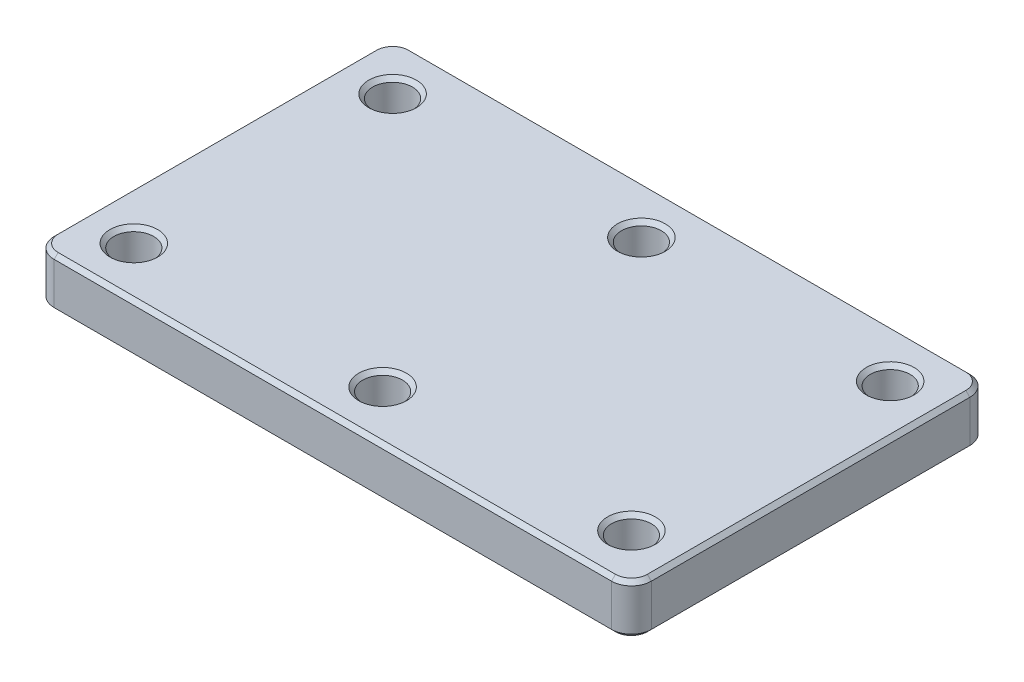
SolidWorks part; units mm, degrees
ref_plane "前基準面" through (0, 0, 0) normal (0, 0, 1) x (1, 0, 0)
ref_plane "上基準面" through (0, 0, 0) normal (0, 1, 0) x (1, 0, 0)
ref_plane "右基準面" through (0, 0, 0) normal (1, 0, 0) x (0, 0, -1)
ref_plane "平面1"
sketch "草圖1" plane through (0, 0, 0) normal (0, 1, 0) x (-1, 0, 0)
  line L0 (150, -90) -> (-150, -90)
  line L1 (-150, -90) -> (-150, 90)
  line L2 (-150, 90) -> (150, 90)
  line L3 (150, 90) -> (150, -90)
  dimension "D1" = 300
  dimension "D2" = 180
extrude "擠出1" add sketch "草圖1" along normal blind 25
fillet "圓角1" radius 10 4 edges at (-150, 12.5, -90) (-150, 12.5, 90) (150, 12.5, -90) (150, 12.5, 90)
sketch "草圖2" plane through (0, 25, 0) normal (0, 1, 0) x (-1, 0, 0)
  circle A0 centre (125, 65) radius 10
  circle A1 centre (125, -65) radius 10
  circle A2 centre (0, -65) radius 10
  circle A3 centre (0, 65) radius 10
  circle A4 centre (-125, 65) radius 10
  circle A5 centre (-125, -65) radius 10
  dimension "D3" = 20
  dimension "D4" = 20
  dimension "D5" = 20
  dimension "D6" = 20
  dimension "D7" = 20
  dimension "D8" = 20
  dimension "D1" = 250
  dimension "D2" = 130
extrude "擠出2" cut sketch "草圖2" against normal blind 25 contours A5 | A4 | A3 | A2 | A1 | A0
chamfer "倒角1" distance 2 distance2 2 28 edges at (0, 25, 90) (147.0711, 25, 87.0711) (150, 25, 0) (147.0711, 25, -87.0711) (0, 25, -90) (-147.0711, 25, -87.0711) (-150, 25, 0) (-147.0711, 25, 87.0711) (0, 0, 90) (-147.0711, 0, 87.0711) (-150, 0, 0) (-147.0711, 0, -87.0711) (0, 0, -90) (147.0711, 0, -87.0711) (150, 0, 0) (147.0711, 0, 87.0711) (-125, 25, 75) (-125, 25, -55) (0, 25, -55) (0, 25, 75) (125, 25, -55) (125, 25, 75) (125, 0, 75) (0, 0, 75) (-125, 0, 75) (-125, 0, -55) (0, 0, -55) (125, 0, -55)
